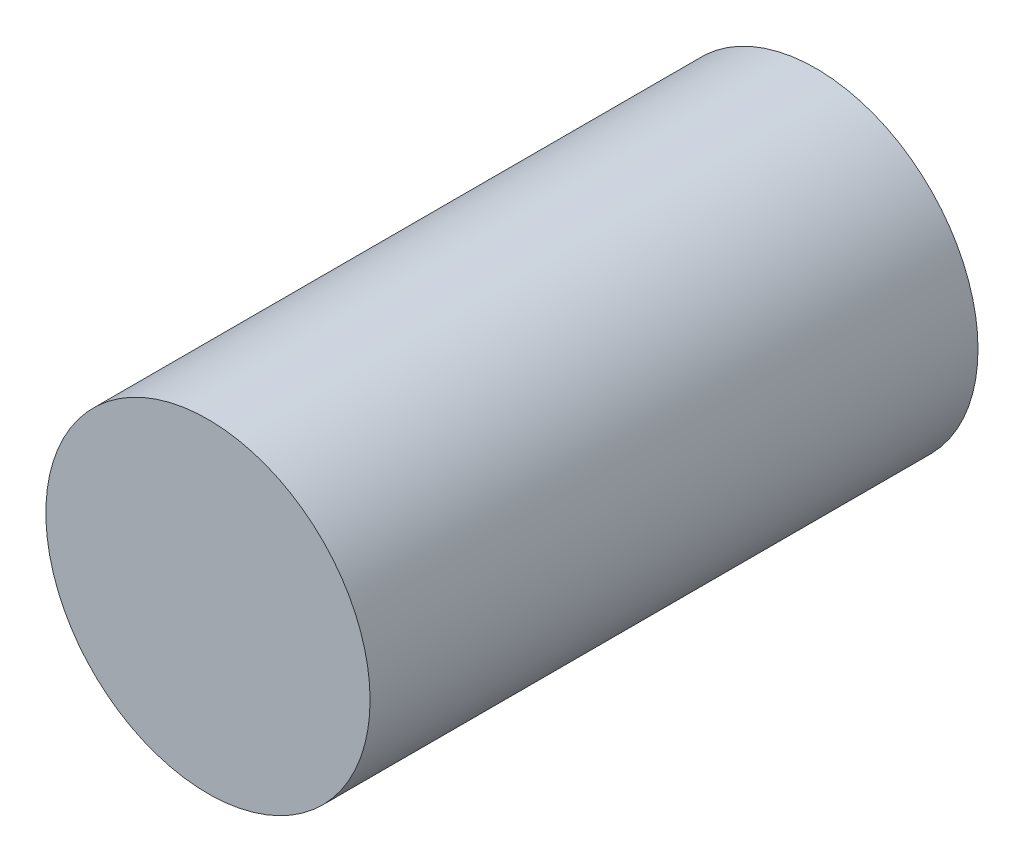
SolidWorks part; units mm, degrees
ref_plane "前视基准面" through (0, 0, 0) normal (0, 0, 1) x (1, 0, 0)
ref_plane "上视基准面" through (0, 0, 0) normal (0, 1, 0) x (1, 0, 0)
ref_plane "右视基准面" through (0, 0, 0) normal (1, 0, 0) x (0, 0, -1)
other "Configuration Table"
sketch "草图1" plane through (0, 0, 0) normal (0, 0, 1) x (1, 0, 0)
  line L0 (0, -95) -> (432, -95)
  line L1 (432, -95) -> (432, 235)
  line L2 (432, 235) -> (0, 235)
  line L3 (0, 235) -> (0, -95)
extrude "凸台-拉伸1" add sketch "草图1" along normal blind 12
sketch "草图2" plane through (0, 0, 12) normal (0, 0, 1) x (1, 0, 0)
  circle A0 centre (20, -42) radius 3.2
extrude "切除-拉伸1" cut sketch "草图2" against normal through all flip side to cut
sketch "草图3" plane through (0, 0, 0) normal (0, 0, 1) x (1, 0, 0)
  circle A0 centre (412, -42) radius 3.2
sketch "草图4" plane through (0, 0, 0) normal (0, 0, 1) x (1, 0, 0)
  circle A0 centre (20, 88) radius 3.2
sketch "草图5" plane through (0, 0, 0) normal (0, 0, 1) x (1, 0, 0)
  circle A0 centre (412, 88) radius 3.2
